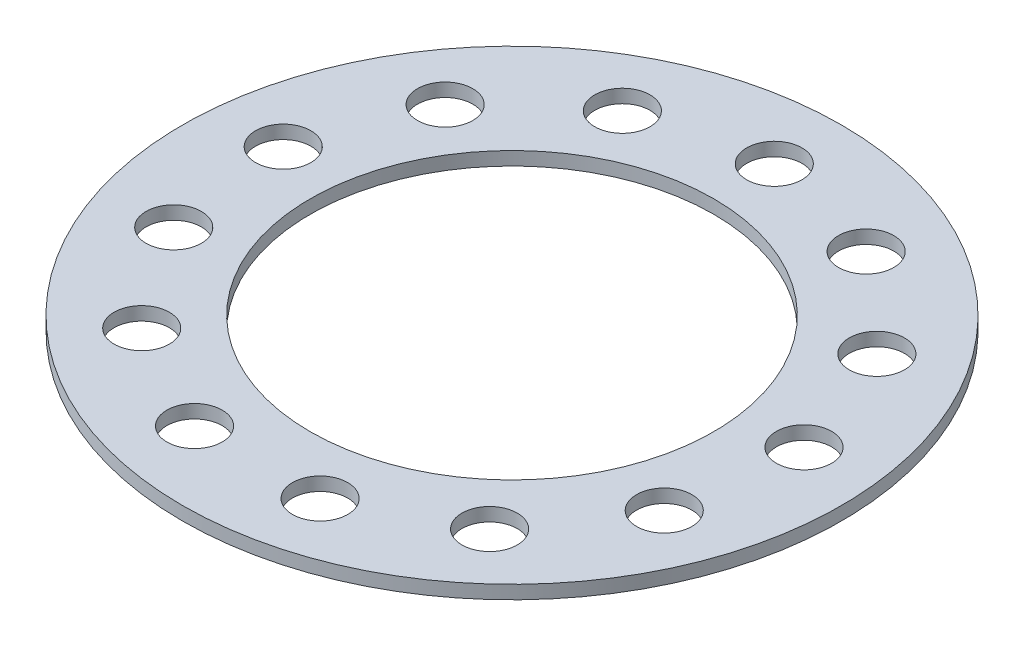
SolidWorks part; units mm, degrees
material "Copper"
ref_plane "Front Plane" through (0, 0, 0) normal (0, 0, 1) x (1, 0, 0)
ref_plane "Top Plane" through (0, 0, 0) normal (0, 1, 0) x (1, 0, 0)
ref_plane "Right Plane" through (0, 0, 0) normal (1, 0, 0) x (0, 0, -1)
sketch "Sketch1" plane through (0, 0, 0) normal (0, 1, 0) x (1, 0, 0)
  circle A0 centre (0, 0) radius 24.5
  circle A9 centre (0, 0) radius 15
  point P7 (0, 24.5)
  dimension "D1" = 49
  dimension "D2" = 30
extrude "Boss-Extrude1" add sketch "Sketch1" along normal blind 1
sketch "Sketch3" plane through (0, 1, 0) normal (0, 1, 0) x (1, 0, 0)
  line L53 (0, 19.5) -> (0, 24.5) construction
  circle A0 centre (0, 19.5) radius 2.055
  circle A3 centre (0, 0) radius 24.5 construction
  dimension "D1" = 4.11
  dimension "D2" = 5
extrude "Cut-Extrude1" cut sketch "Sketch3" against normal through all
pattern_circular "CirPattern1" count 13 over 360 about axis through (0, 0, 0) along (0, 1, 0) of "Cut-Extrude1"
equation "\"shaft_diameter\"=12"
equation "\"outerdiameter\"=49"
equation "\"numberofbars\"= 13"
equation "\"t\"= 20"
equation "\"width\"=1.5"
equation "\"bardiameter\"= 4.11"
equation "\"D1@Sketch1\"=\"outerdiameter\""
equation "\"centerdepth\"= 5"
equation "\"D1@Boss-Extrude1\"= \"t\""
equation "\"key_width\"=4"
equation "\"key_height\"= 2.5"
equation "\"D2@Sketch3\"=\"centerdepth\""
equation "\"RF1\"= 0.25"
equation "\"D1@Sketch3\"=\"bardiameter\""
equation "\"D1@CirPattern1\"=\"numberofbars\""
